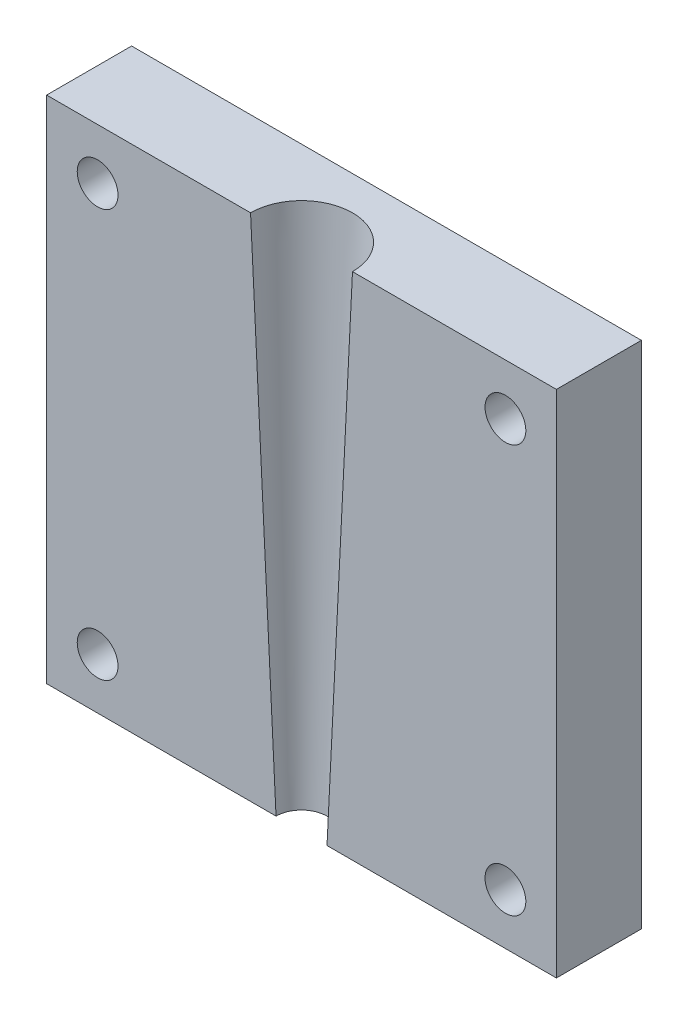
SolidWorks part; units mm, degrees
ref_plane "Front Plane" through (0, 0, 0) normal (0, 0, 1) x (1, 0, 0)
ref_plane "Top Plane" through (0, 0, 0) normal (0, 1, 0) x (1, 0, 0)
ref_plane "Right Plane" through (0, 0, 0) normal (1, 0, 0) x (0, 0, -1)
sketch "Sketch1" plane through (0, 0, 0) normal (0, 0, 1) x (1, 0, 0)
  line L1 (0, 0) -> (30, 0)
  line L2 (0, 0) -> (0, -30)
  line L3 (0, -30) -> (30, -30)
  line L4 (30, 0) -> (30, -30)
  dimension "D1" = 30
  dimension "D2" = 30
extrude "Boss-Extrude1" add sketch "Sketch1" along normal blind 5
sketch "Sketch2" plane through (0, 0, 0) normal (0, 1, 0) x (1, 0, 0)
  line L0 (30, -5) -> (0, -5) construction
  line L3 (12, -5) -> (18, -5)
  arc A0 (18, -5) -> (12, -5) centre (15, -5) ccw
  dimension "D1" = 6
sketch "Sketch3" plane through (0, -30, 0) normal (0, -1, 0) x (1, 0, 0)
  line L0 (13.5, 5) -> (16.5, 5)
  arc A0 (13.5, 5) -> (16.5, 5) centre (15, 5) ccw
  dimension "D1" = 3
loft "Cut-Loft1" cut profiles "Sketch2", "Sketch3"
sketch "Sketch4" plane through (0, 0, 0) normal (0, 0, -1) x (-1, 0, 0)
  line L0 (-30, 0) -> (0, 0) construction
  line L2 (-30, -30) -> (-30, 0) construction
  line L3 (0, 0) -> (0, -30) construction
  line L4 (0, -30) -> (-30, -30) construction
  point P0 (-27, -3)
  point P1 (-27, -27)
  point P2 (-3, -27)
  point P3 (-3, -3)
  point P8 (-30, -3.4208)
  dimension "D1" = 3
  dimension "D2" = 3
  dimension "D3" = 3
  dimension "D4" = 3
  dimension "D5" = 3
  dimension "D6" = 3
  dimension "D7" = 3
  dimension "D8" = 3
hole_wizard "CBORE for M2 Pan Head Machine Screw1" positions "Sketch7" profile "Sketch6" counterbore size "M2" standard "ANSI Metric" end condition through all
sketch "Sketch7" plane through (0, 0, 0) normal (0, 0, -1) x (-1, 0, 0)
  point P0 (-27, -3)
  point P3 (-3, -3)
  point P6 (-3, -27)
  point P9 (-27, -27)
sketch "Sketch6" plane through (27, -3, 0) normal (1, 0, 0) x (0, 1, 0)
  line L0 (0, 0) -> (0, 5)
  line L1 (0, 5) -> (1.2, 5)
  line L3 (1.2, 5) -> (1.2, 1.6)
  line L4 (1.2, 1.6) -> (2.5, 1.6)
  line L5 (2.5, 1.6) -> (2.5, 0)
  line L7 (2.5, 0) -> (0, 0)
  line L11 (0, -6.35) -> (0, 107.95) construction
  dimension "Thru Hole Dia." = 2.4
  dimension "Thru Hole Depth" = 5
  dimension "C'Bore Dia." = 5
  dimension "C'Bore Depth" = 1.6
